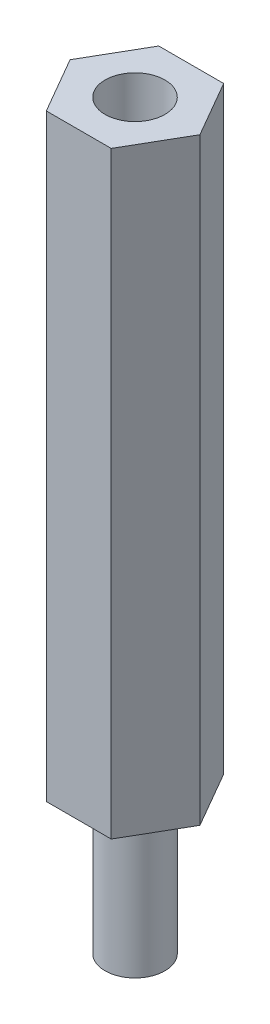
SolidWorks part; units mm, degrees
ref_plane "Front Plane" through (0, 0, 0) normal (0, 0, 1) x (1, 0, 0)
ref_plane "Top Plane" through (0, 0, 0) normal (0, 1, 0) x (1, 0, 0)
ref_plane "Right Plane" through (0, 0, 0) normal (1, 0, 0) x (0, 0, -1)
sketch "Sketch1" plane through (0, 0, 0) normal (0, 1, 0) x (1, 0, 0)
  line L1 (1.3568, 2.35) -> (-1.3568, 2.35)
  line L2 (-1.3568, 2.35) -> (-2.7135, 0)
  line L3 (-2.7135, 0) -> (-1.3568, -2.35)
  line L4 (-1.3568, -2.35) -> (1.3568, -2.35)
  line L5 (1.3568, -2.35) -> (2.7135, 0)
  line L6 (2.7135, 0) -> (1.3568, 2.35)
  circle A0 centre (0, 0) radius 2.35 construction
  circle A1 centre (0, 0) radius 1.25
  dimension "D2" = 2.5
  dimension "D1" = 4.7
extrude "Boss-Extrude1" add sketch "Sketch1" along normal blind 25
sketch "Sketch2" plane through (0, 0, 0) normal (0, 1, 0) x (1, 0, 0)
  circle A0 centre (0, 0) radius 1.25 construction
  circle A1 centre (0, 0) radius 1.25
extrude "Boss-Extrude3" add sketch "Sketch2" against normal blind 6 and the other way blind 19
